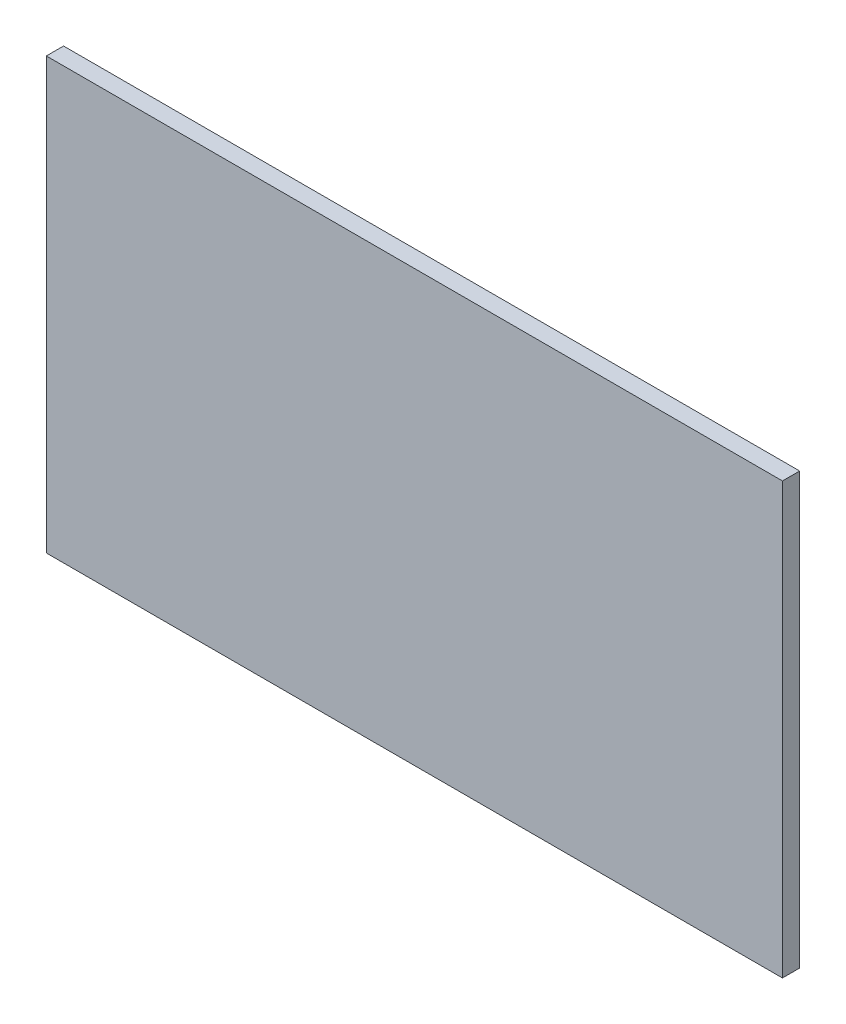
SolidWorks part; units mm, degrees
material "Plain Carbon Steel"
ref_plane "Front Plane" through (0, 0, 0) normal (0, 0, 1) x (1, 0, 0)
ref_plane "Top Plane" through (0, 0, 0) normal (0, 1, 0) x (1, 0, 0)
ref_plane "Right Plane" through (0, 0, 0) normal (1, 0, 0) x (0, 0, -1)
sketch "Sketch1" plane through (0, 0, 0) normal (0, 0, 1) x (1, 0, 0)
  line L0 (550, -500) -> (1105, -500) construction
  line L1 (-605, 500) -> (1105, 500)
  line L2 (-605, 500) -> (-605, -500)
  line L3 (-605, -500) -> (1105, -500)
  line L4 (1105, 500) -> (1105, -500)
  line L5 (550, 500) -> (1105, 500) construction
  line L6 (1105, -500) -> (1105, 500) construction
  line L7 (-505, -350) -> (-505, 350) construction
  dimension "D1" = 100
extrude "Boss-Extrude1" add sketch "Sketch1" along normal blind 40 contours L1 L4 L3 L2
